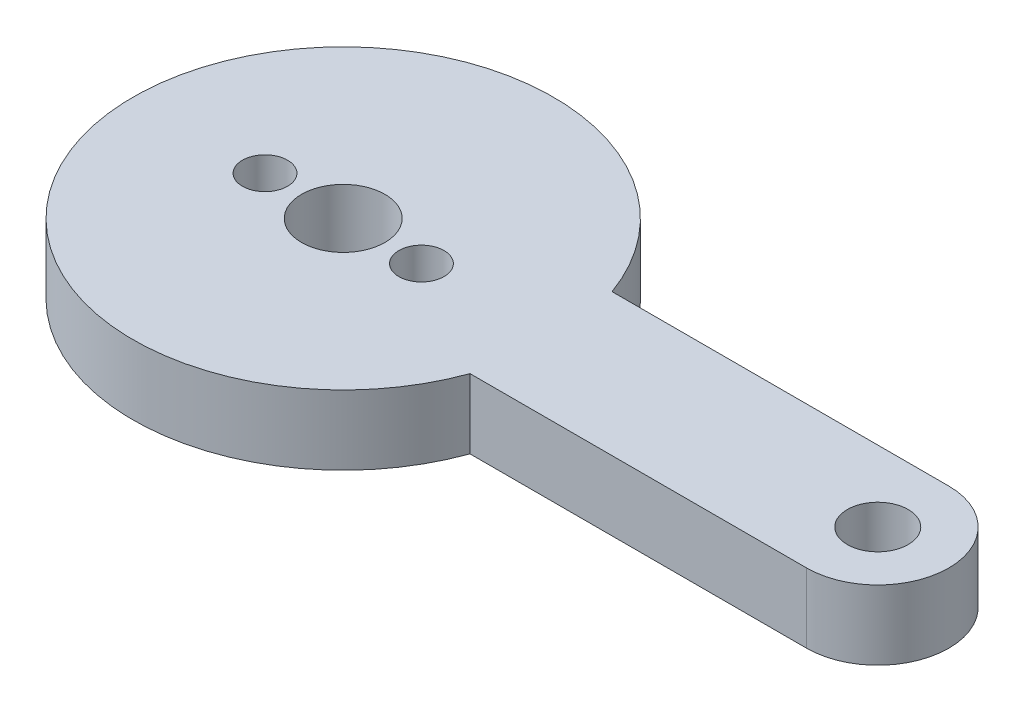
SolidWorks part; units mm, degrees
ref_plane "前视基准面" through (0, 0, 0) normal (0, 0, 1) x (1, 0, 0)
ref_plane "上视基准面" through (0, 0, 0) normal (0, 1, 0) x (1, 0, 0)
ref_plane "右视基准面" through (0, 0, 0) normal (1, 0, 0) x (0, 0, -1)
sketch "草图2" plane through (0, 0, 0) normal (0, 1, 0) x (1, 0, 0)
  line L0 (0, 0) -> (0, 12.09) construction
  line L1 (0, 0) -> (30.75, 0) construction
  line L2 (11.3789, 4.0851) -> (30.75, 4.0851)
  line L3 (30.75, -4.0851) -> (11.3789, -4.0851)
  circle A1 centre (0, 0) radius 12.09
  circle A2 centre (0, 0) radius 1.75
  circle A7 centre (0, 0) radius 12.09
  circle A10 centre (0, 0) radius 12.09
  circle A13 centre (0, 0) radius 12.09
  circle A16 centre (0, 0) radius 12.09
  circle A19 centre (0, 0) radius 12.09
  circle A22 centre (0, 0) radius 12.09
  circle A25 centre (0, 0) radius 12.09
  circle A28 centre (0, 0) radius 12.09
  circle A31 centre (0, 0) radius 12.09
  circle A34 centre (0, 0) radius 12.09
  circle A37 centre (0, 0) radius 12.09
  circle A40 centre (0, 0) radius 12.09
  circle A43 centre (0, 0) radius 12.09
  circle A46 centre (0, 0) radius 12.09
  circle A49 centre (0, 0) radius 12.09
  circle A52 centre (0, 0) radius 12.09
  circle A55 centre (0, 0) radius 12.09
  circle A58 centre (0, 0) radius 12.09
  circle A61 centre (0, 0) radius 12.09
  circle A64 centre (0, 0) radius 12.09
  circle A67 centre (0, 0) radius 12.09
  circle A70 centre (0, 0) radius 12.09
  circle A73 centre (0, 0) radius 12.09
  arc A74 (30.75, 4.0851) -> (30.75, -4.0851) centre (30.75, 0) cw
  circle A75 centre (30.75, 0) radius 1.75
  point P175 (0, 0)
  dimension "D1" = 3.5
  dimension "D2" = 24.18
  dimension "D9" = 3.5
  dimension "D10" = 4.0851
  dimension "D8" = 30.75
  dimension "D7" = 24
extrude "凸台-拉伸1" add sketch "草图2" along normal blind 4
sketch "草图3" plane through (0, 4, 0) normal (0, 1, 0) x (1, 0, 0)
  line L0 (-4.5, 0) -> (4.5, 0) construction
  circle A0 centre (0, 0) radius 2.4
  circle A1 centre (4.5, 0) radius 1.3
  circle A2 centre (-4.5, 0) radius 1.3
  point P8 (0, 0)
  dimension "D1" = 4.8
  dimension "D2" = 2.6
  dimension "D3" = 2.6
  dimension "D4" = 9
extrude "切除-拉伸1" cut sketch "草图3" against normal through all
